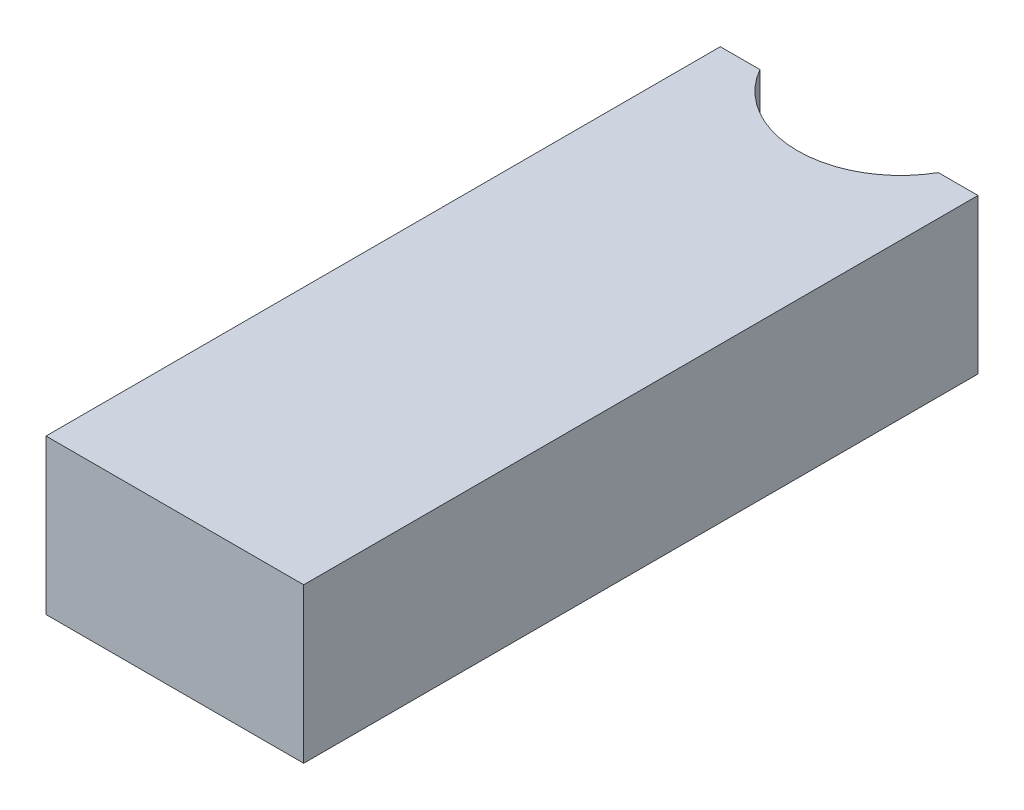
SolidWorks part; units mm, degrees
material "Custom Plastic"
ref_plane "X-Y Datum" through (0, 0, 0) normal (0, 0, 1) x (1, 0, 0)
ref_plane "X-Z Datum" through (0, 0, 0) normal (0, 1, 0) x (1, 0, 0)
ref_plane "Y-Z Datum" through (0, 0, 0) normal (1, 0, 0) x (0, 0, -1)
sketch "Sketch1" plane through (0, 0, 0) normal (0, 0, 1) x (1, 0, 0)
  line L1 (-15.875, 9.525) -> (15.875, 9.525)
  line L2 (-15.875, 9.525) -> (-15.875, -9.525)
  line L3 (-15.875, -9.525) -> (15.875, -9.525)
  line L4 (15.875, 9.525) -> (15.875, -9.525)
  line L5 (-15.875, 9.525) -> (15.875, -9.525) construction
  line L6 (-15.875, -9.525) -> (15.875, 9.525) construction
  point P0 (0, 0)
  dimension "D1" = 31.75
  dimension "D2" = 19.05
extrude "Boss-Extrude1" add sketch "Sketch1" along normal blind 83.0834
sketch "Sketch2" plane through (0, 9.525, 0) normal (0, 1, 0) x (1, 0, 0)
  circle A0 centre (0, 6.35) radius 12.7
  point P2 (0, -6.35)
  dimension "D1" = 25.4
  dimension "D2" = 6.35
extrude "Cut-Extrude1" cut sketch "Sketch2" against normal through all
